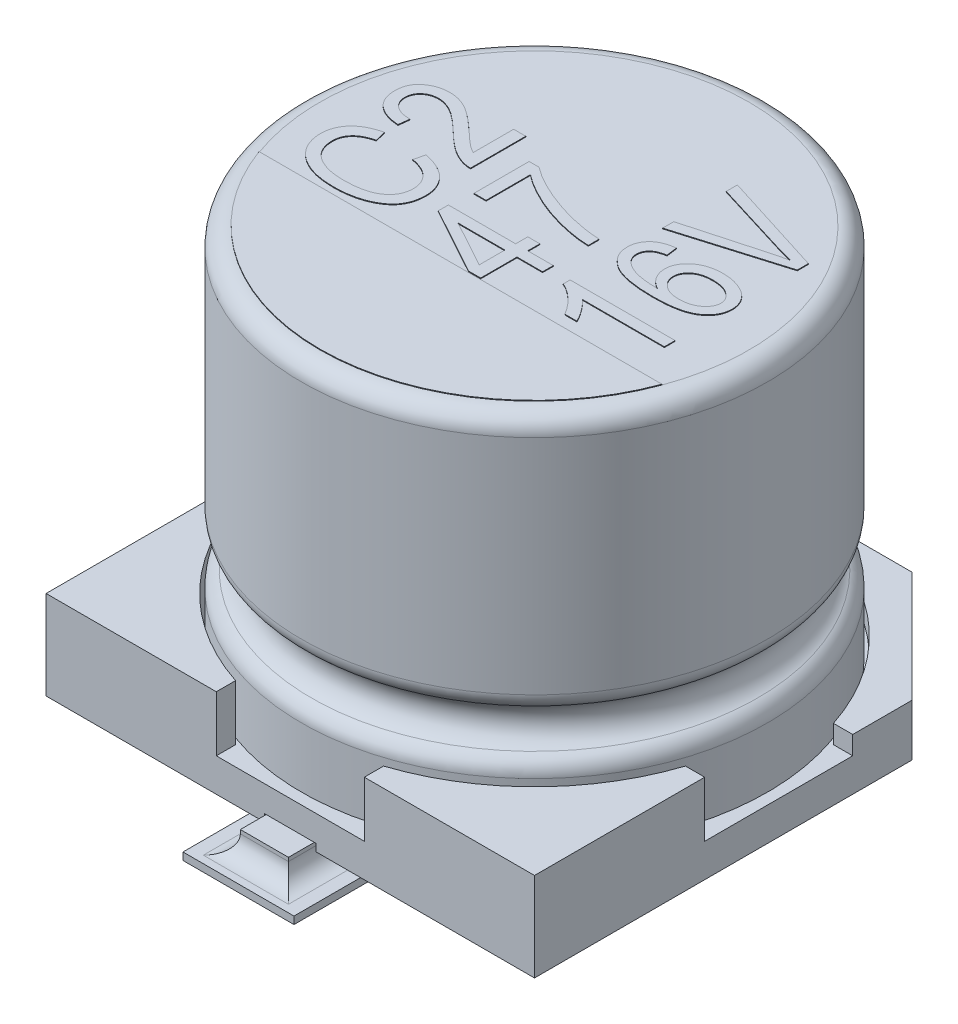
SolidWorks part; units mm, degrees
material "PA Type 6"
ref_plane "Front Plane" through (0, 0, 0) normal (0, 0, 1) x (1, 0, 0)
ref_plane "Top Plane" through (0, 0, 0) normal (0, 1, 0) x (1, 0, 0)
ref_plane "Right Plane" through (0, 0, 0) normal (1, 0, 0) x (0, 0, -1)
ref_plane "Plane1" through (0, 0.3, 0) normal (0, 1, 0) x (1, 0, 0)
sketch "Sketch1" plane through (0, 0.3, 0) normal (0, 1, 0) x (1, 0, 0)
  line L0 (-55, 0) -> (55, 0) construction
  line L1 (-3.3, -3.3) -> (3.3, -3.3)
  line L2 (-3.3, -3.3) -> (-3.3, 3.3)
  line L3 (-3.3, 3.3) -> (3.3, 3.3)
  line L4 (3.3, -3.3) -> (3.3, 3.3)
  line L5 (0, -55) -> (0, 55) construction
  dimension "D1" = 6.6
  dimension "D2" = 6.6
  dimension "D3" = 3.3
  dimension "D4" = 3.3
extrude "Boss-Extrude1" add sketch "Sketch1" along normal blind 1.2
sketch "Sketch2" plane through (0, 1.5, 0) normal (0, 1, 0) x (1, 0, 0)
  line L0 (-3.3, 1) -> (-3.0397, 1)
  line L1 (-3.3, 3.3) -> (-3.3, -3.3) construction
  line L2 (3.3, -3.3) -> (3.3, 3.3) construction
  line L3 (3.3, 1) -> (3.3, -1)
  line L4 (3.3, -1) -> (3.0397, -1)
  line L5 (-3.3, -1) -> (-3.3, 1)
  line L6 (3.3, 3.3) -> (-3.3, 3.3) construction
  line L7 (-1, 3.3) -> (1, 3.3)
  line L8 (-1, 3.3) -> (-1, 3.0397)
  line L9 (-1, -3.3) -> (1, -3.3)
  line L10 (1, 3.3) -> (1, 3.0397)
  line L11 (-3.3, -3.3) -> (3.3, -3.3) construction
  line L15 (-3.0397, -1) -> (-3.3, -1)
  line L16 (-1, -3.0397) -> (-1, -3.3)
  line L17 (1, -3.0397) -> (1, -3.3)
  line L19 (3.0397, 1) -> (3.3, 1)
  line L20 (-55, 0) -> (55, 0) construction
  line L22 (0, -55) -> (0, 55) construction
  arc A0 (3.0397, 1) -> (1, 3.0397) centre (0, 0) ccw
  arc A1 (-1, 3.0397) -> (-3.0397, 1) centre (0, 0) ccw
  arc A2 (-3.0397, -1) -> (-1, -3.0397) centre (0, 0) ccw
  arc A3 (1, -3.0397) -> (3.0397, -1) centre (0, 0) ccw
  dimension "D1" = 6.4
  dimension "D2" = 1
  dimension "D3" = 1
  dimension "D4" = 1
extrude "Cut-Extrude1" cut sketch "Sketch2" against normal blind 0.75
sketch "Sketch3" plane through (0, 0, 0) normal (1, 0, 0) x (0, 0, -1)
  line L0 (0, 55) -> (0, -55) construction
  line L1 (3.3, 1.5) -> (0, 1.5)
  line L2 (3.3, 1.5) -> (3.3, 1)
  line L3 (3.3, 1) -> (0, 1)
  line L4 (0, 1.5) -> (0, 1)
  dimension "D1" = 0.5
extrude "Cut-Extrude2" cut sketch "Sketch3" against normal through all and the other way through all
chamfer "Chamfer1" distance 1.5 angle 45 2 edges at (-3.3, 0.65, -3.3) (3.3, 0.65, -3.3)
sketch "Sketch4" plane through (0, 0, 0) normal (1, 0, 0) x (0, 0, -1)
  line L0 (0, 0) -> (0, 7.4696) construction
  line L1 (0, 55) -> (0, -55) construction
  line L2 (0, 0.75) -> (0, 5.8)
  line L3 (-1, 0.75) -> (1, 0.75) construction
  line L4 (0, 5.8) -> (-2.9, 5.8)
  line L5 (-3.15, 5.55) -> (-3.15, 2.5399)
  line L6 (-3.15, 1.5601) -> (-3.15, 0.75)
  line L7 (-3.15, 0.75) -> (0, 0.75)
  line L9 (55, 0) -> (-55, 0) construction
  arc A0 (-2.9, 5.8) -> (-3.15, 5.55) centre (-2.9, 5.55) ccw
  arc A1 (-3.0136, 2.3172) -> (-3.0136, 1.7828) centre (-3.15, 2.05) cw
  arc A2 (-3.0136, 1.7828) -> (-3.15, 1.5601) centre (-2.9, 1.5601) ccw
  arc A3 (-3.15, 2.5399) -> (-3.0136, 2.3172) centre (-2.9, 2.5399) ccw
  point P20 (-3.15, 1.75)
  dimension "D2" = 0.3
  dimension "D5" = 0.25
  dimension "D6" = 0.25
  dimension "D1" = 6.3
  dimension "D3" = 1
  dimension "D4" = 5.8
revolve "Revolve1" add sketch "Sketch4" angle 360 about L0
sketch "Sketch6" plane through (0, 0.3, 0) normal (0, -1, 0) x (1, 0, 0)
  line L0 (0, -55) -> (0, 55) construction
  line L1 (-0.325, -1.225) -> (-0.325, -3.65)
  line L2 (-0.325, -3.65) -> (0.325, -3.65)
  line L3 (0.325, -3.65) -> (0.325, -1.225)
  line L4 (-0.325, 1.225) -> (-0.325, 3.65)
  line L5 (-0.325, 3.65) -> (0.325, 3.65)
  line L6 (0.325, 3.65) -> (0.325, 1.225)
  line L7 (55, 0) -> (-55, 0) construction
  line L8 (-3.3, 3.3) -> (3.3, 3.3) construction
  line L9 (1.8, -3.3) -> (-1.8, -3.3) construction
  arc A0 (-0.325, 1.225) -> (0.325, 1.225) centre (0, 1.225) ccw
  arc A1 (0.325, -1.225) -> (-0.325, -1.225) centre (0, -1.225) ccw
  dimension "D1" = 0.65
  dimension "D2" = 2.45
  dimension "D3" = 1.225
  dimension "D4" = 0.35
  dimension "D5" = 0.35
sketch "Sketch7" plane through (0, 0.3, 0) normal (0, -1, 0) x (1, 0, 0)
  line L0 (-0.35, 3.3) -> (0.35, 3.3)
  line L1 (-3.3, 3.3) -> (3.3, 3.3) construction
  line L2 (0.35, 3.3) -> (0.4987, 1.2614)
  line L3 (-0.4987, 1.2614) -> (-0.35, 3.3)
  line L4 (-0.35, -3.3) -> (0.35, -3.3)
  line L5 (1.8, -3.3) -> (-1.8, -3.3) construction
  line L6 (-0.4987, -1.2614) -> (-0.35, -3.3)
  line L7 (0.4987, -1.2614) -> (0.35, -3.3)
  line L8 (0, -55) -> (0, 55) construction
  arc A0 (-0.4987, 1.2614) -> (0.4987, 1.2614) centre (0, 1.225) ccw
  arc A1 (0.4987, -1.2614) -> (-0.4987, -1.2614) centre (0, -1.225) ccw
  dimension "D3" = 1
  dimension "D1" = 0.7
  dimension "D2" = 0.35
extrude "Cut-Extrude3" cut sketch "Sketch7" against normal blind 0.1
extrude "Boss-Extrude4" add sketch "Sketch6" against normal blind 0.1 and the other way blind 0.3
sketch "Sketch8" plane through (0, 0.3, 0) normal (0, -1, 0) x (1, 0, 0)
  line L0 (0, -55) -> (0, 55) construction
  line L1 (-2, 2) -> (2, 2) construction
  line L2 (-2, 2) -> (-2, -2) construction
  line L3 (-2, -2) -> (2, -2) construction
  line L4 (2, 2) -> (2, -2) construction
  line L5 (55, 0) -> (-55, 0) construction
  circle A0 centre (-2, 2) radius 0.5
  circle A1 centre (2, 2) radius 0.5
  circle A2 centre (2, -2) radius 0.5
  circle A3 centre (-2, -2) radius 0.5
  dimension "D1" = 1
  dimension "D2" = 2
  dimension "D3" = 2
  dimension "D4" = 2
  dimension "D5" = 2
extrude "Boss-Extrude5" add sketch "Sketch8" along normal blind 0.3
sketch "Sketch9" plane through (0, 0, 0) normal (0, 1, 0) x (1, 0, 0)
  line L0 (-3.19, 0) -> (3.19, 0) construction
  line L1 (-0.75, 4) -> (0.75, 4)
  line L2 (-0.75, 4) -> (-0.75, 2)
  line L3 (-0.75, 2) -> (0.75, 2)
  line L4 (0.75, 4) -> (0.75, 2)
  line L5 (-0.75, -2) -> (0.75, -2)
  line L6 (-0.75, -2) -> (-0.75, -4)
  line L7 (-0.75, -4) -> (0.75, -4)
  line L8 (0.75, -2) -> (0.75, -4)
  line L9 (0, -3.19) -> (0, 3.19) construction
  dimension "D1" = 2
  dimension "D2" = 4
  dimension "D3" = 1.5
  dimension "D4" = 0.75
  dimension "D5" = 4
extrude "Boss-Extrude6" add sketch "Sketch9" along normal blind 0.1
fillet "Fillet1" radius 0.25 6 edges at (-0.325, 0.1, -2.825) (0, 0.1, -3.65) (0.325, 0.1, -2.825) (-0.325, 0.1, 2.825) (0.325, 0.1, 2.825) (0, 0.1, 3.65)
sketch "Sketch10" plane through (0, 5.8, 0) normal (0, 1, 0) x (1, 0, 0)
  line L0 (-2.7221, -1) -> (2.7221, -1)
  line L1 (-3.19, 0) -> (3.19, 0) construction
  line L2 (-1.1, -1) -> (-1.1, 2) construction
  line L3 (0, -3.19) -> (0, 3.19) construction
  line L4 (0.6, -1) -> (0.6, 2) construction
  line L6 (2.3, -1) -> (2.3, 2) construction
  circle A0 centre (0, 0) radius 2.9 construction
  arc A1 (-2.7221, -1) -> (2.7221, -1) centre (0, 0) ccw
  text T0 "C2" font "@Adobe Heiti Std R" height 1.4
  text T1 "47" font "@Adobe Heiti Std R" height 1.4
  text T2 "16V" font "@Adobe Heiti Std R" height 1.4
  dimension "D1" = 1
  dimension "D2" = 1.1
  dimension "D3" = 1.7
  dimension "D4" = 1.7
  dimension "D5" = 3
extrude "Boss-Extrude7" add sketch "Sketch10" along normal blind 0.01
